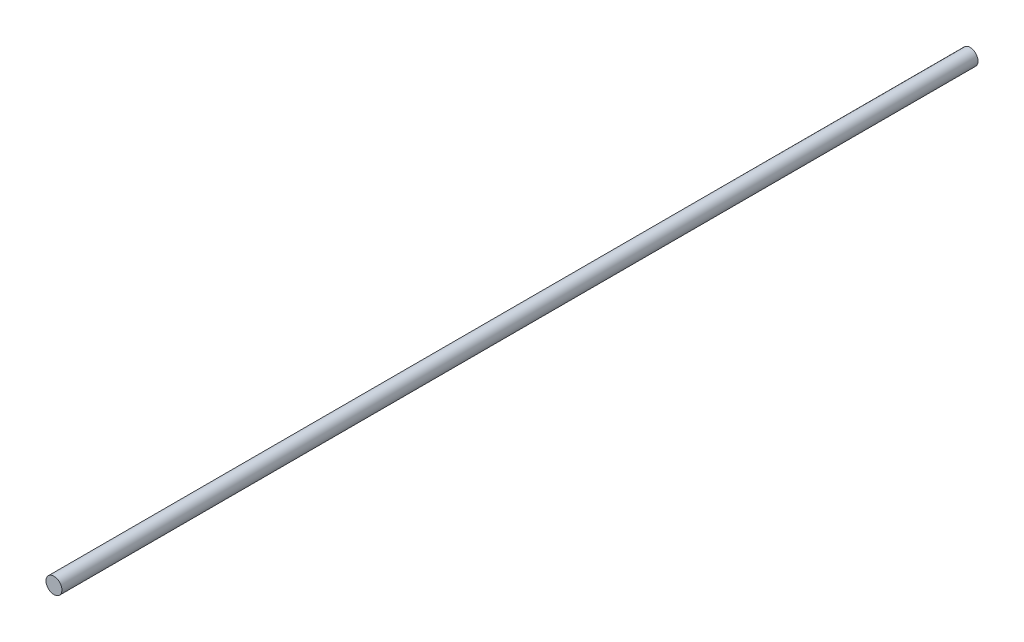
SolidWorks part; units mm, degrees
material "Plain Carbon Steel"
ref_plane "Front Plane" through (0, 0, 0) normal (0, 0, 1) x (1, 0, 0)
ref_plane "Top Plane" through (0, 0, 0) normal (0, 1, 0) x (1, 0, 0)
ref_plane "Right Plane" through (0, 0, 0) normal (1, 0, 0) x (0, 0, -1)
sketch "Sketch1" plane through (0, 0, 0) normal (0, 0, 1) x (1, 0, 0)
  circle A0 centre (0, 0) radius 4
  dimension "D1" = 8
extrude "Boss-Extrude1" add sketch "Sketch1" along normal blind 460
equation "\"D1@Boss-Extrude1\"=460"
